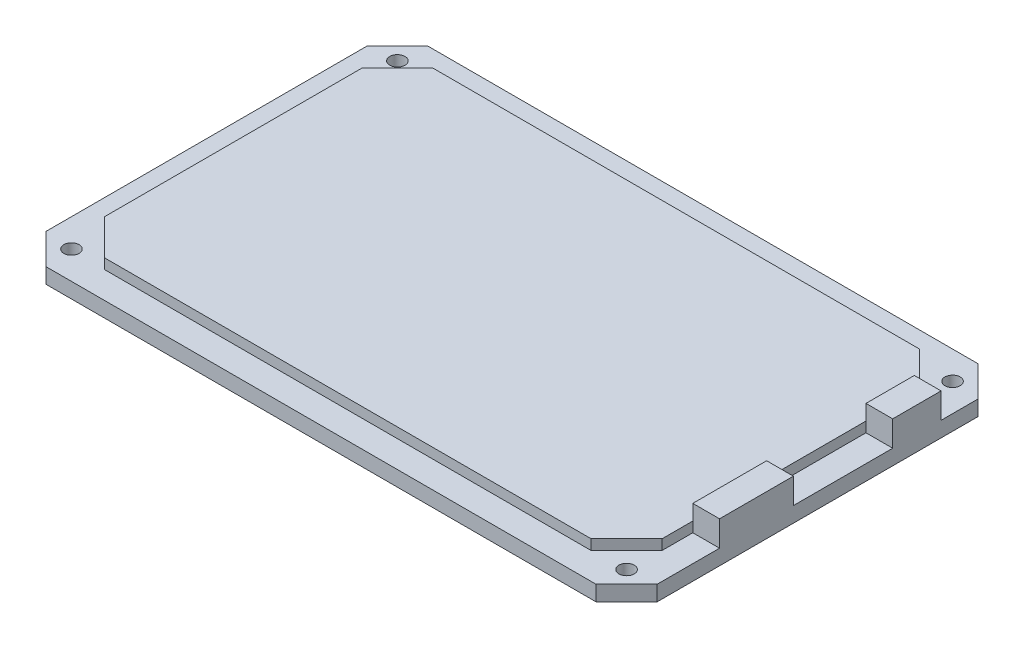
SolidWorks part; units mm, degrees
ref_plane "Front Plane" through (0, 0, 0) normal (0, 0, 1) x (1, 0, 0)
ref_plane "Top Plane" through (0, 0, 0) normal (0, 1, 0) x (1, 0, 0)
ref_plane "Right Plane" through (0, 0, 0) normal (1, 0, 0) x (0, 0, -1)
sketch "Sketch1" plane through (0, 0, 0) normal (0, 1, 0) x (1, 0, 0)
  line L1 (-60, -37.5) -> (60, -37.5)
  line L2 (-60, -37.5) -> (-60, 37.5)
  line L3 (-60, 37.5) -> (60, 37.5)
  line L4 (60, -37.5) -> (60, 37.5)
  line L5 (-60, -37.5) -> (60, 37.5) construction
  line L6 (-60, 37.5) -> (60, -37.5) construction
  point P0 (0, 0)
  dimension "D1" = 120
  dimension "D2" = 75
extrude "Boss-Extrude1" add sketch "Sketch1" along normal blind 3
chamfer "Chamfer1" distance 6 angle 45 4 edges at (-60, 1.5, -37.5) (60, 1.5, -37.5) (60, 1.5, 37.5) (-60, 1.5, 37.5)
sketch "Sketch2" plane through (0, 3, 0) normal (0, 1, 0) x (1, 0, 0)
  line L1 (-54.75, -32.25) -> (54.75, -32.25)
  line L2 (-54.75, -32.25) -> (-54.75, 32.25)
  line L3 (-54.75, 32.25) -> (54.75, 32.25)
  line L4 (54.75, -32.25) -> (54.75, 32.25)
  line L5 (-54.75, -32.25) -> (54.75, 32.25) construction
  line L6 (-54.75, 32.25) -> (54.75, -32.25) construction
  point P0 (0, 0)
  dimension "D1" = 109.5
  dimension "D2" = 64.5
extrude "Boss-Extrude2" add sketch "Sketch2" along normal blind 2
chamfer "Chamfer2" distance 7 angle 45 4 edges at (54.75, 4, -32.25) (-54.75, 4, -32.25) (-54.75, 4, 32.25) (54.75, 4, 32.25)
sketch "Sketch3" plane through (0, 3, 0) normal (0, 1, 0) x (1, 0, 0)
  line L0 (-54, -37.5) -> (54, -37.5) construction
  line L1 (-60, 31.5) -> (-60, -31.5) construction
  line L2 (54, 37.5) -> (-54, 37.5) construction
  line L3 (60, -31.5) -> (60, 31.5) construction
  circle A0 centre (-54.5, -32) radius 1.5
  circle A1 centre (-54.5, 32) radius 1.5
  circle A2 centre (54.5, 32) radius 1.5
  circle A3 centre (54.5, -32) radius 1.5
  dimension "D1" = 3
  dimension "D2" = 3
  dimension "D3" = 3
  dimension "D4" = 3
  dimension "D5" = 5.5
  dimension "D6" = 5.5
  dimension "D7" = 5.5
  dimension "D8" = 5.5
  dimension "D9" = 5.5
  dimension "D10" = 5.5
  dimension "D11" = 5.5
  dimension "D12" = 5.5
extrude "Cut-Extrude1" cut sketch "Sketch3" against normal blind 5
sketch "Sketch4" plane through (0, 3, 0) normal (0, 1, 0) x (1, 0, 0)
  line L0 (54.75, -25.25) -> (54.75, 25.25) construction
  line L1 (54.75, 24.25) -> (60, 24.25)
  line L2 (54.75, 24.25) -> (54.75, 14.75)
  line L3 (54.75, 14.75) -> (60, 14.75)
  line L4 (60, 24.25) -> (60, 14.75)
  line L5 (60, -31.5) -> (60, 31.5) construction
  line L7 (54.75, -4.75) -> (60, -4.75)
  line L8 (54.75, -4.75) -> (54.75, -19.25)
  line L9 (54.75, -19.25) -> (60, -19.25)
  line L10 (60, -4.75) -> (60, -19.25)
  point P12 (60, -4.75)
  dimension "D1" = 7.25
  dimension "D2" = 9.5
  dimension "D3" = 19.5
  dimension "D4" = 14.5
extrude "Boss-Extrude3" add sketch "Sketch4" along normal blind 5
